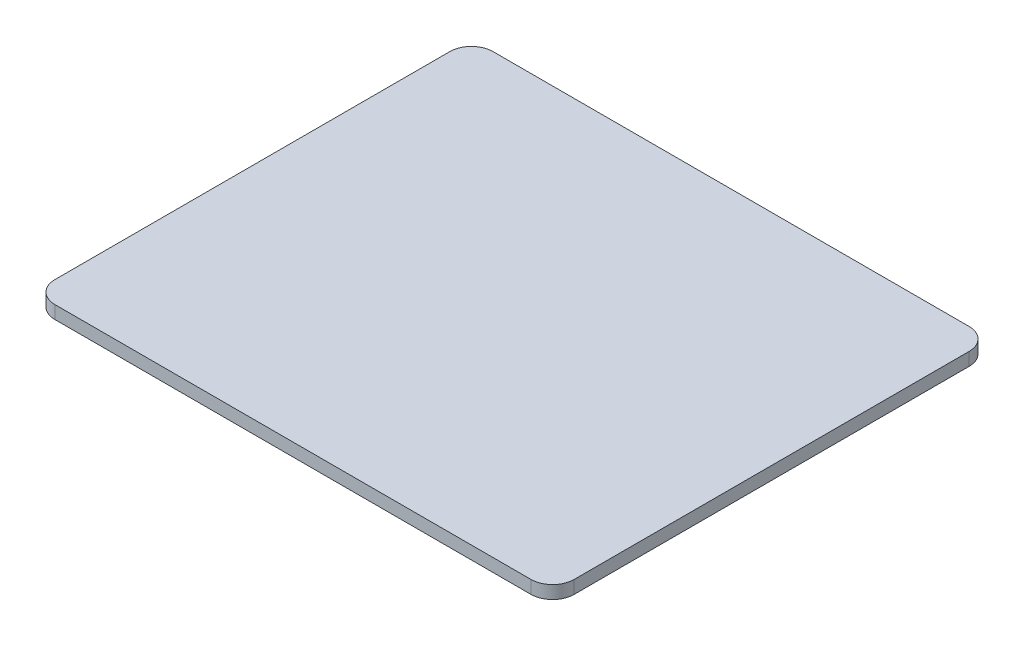
SolidWorks part; units mm, degrees
material "Vidrio"
ref_plane "Alzado" through (0, 0, 0) normal (0, 0, 1) x (1, 0, 0)
ref_plane "Planta" through (0, 0, 0) normal (0, 1, 0) x (1, 0, 0)
ref_plane "Vista lateral" through (0, 0, 0) normal (1, 0, 0) x (0, 0, -1)
sketch "Sketch1" plane through (0, 0, 0) normal (0, 1, 0) x (1, 0, 0)
  line L1 (-60, -50.625) -> (60, -50.625)
  line L2 (-60, -50.625) -> (-60, 50.625)
  line L3 (-60, 50.625) -> (60, 50.625)
  line L4 (60, -50.625) -> (60, 50.625)
  line L5 (-60, -50.625) -> (60, 50.625) construction
  line L6 (-60, 50.625) -> (60, -50.625) construction
  point P0 (0, 0)
  dimension "D1" = 120
extrude "Boss-Extrude1" add sketch "Sketch1" along normal blind 3
fillet "Fillet1" radius 5 4 edges at (-60, 1.5, -50.625) (60, 1.5, -50.625) (60, 1.5, 50.625) (-60, 1.5, 50.625)
